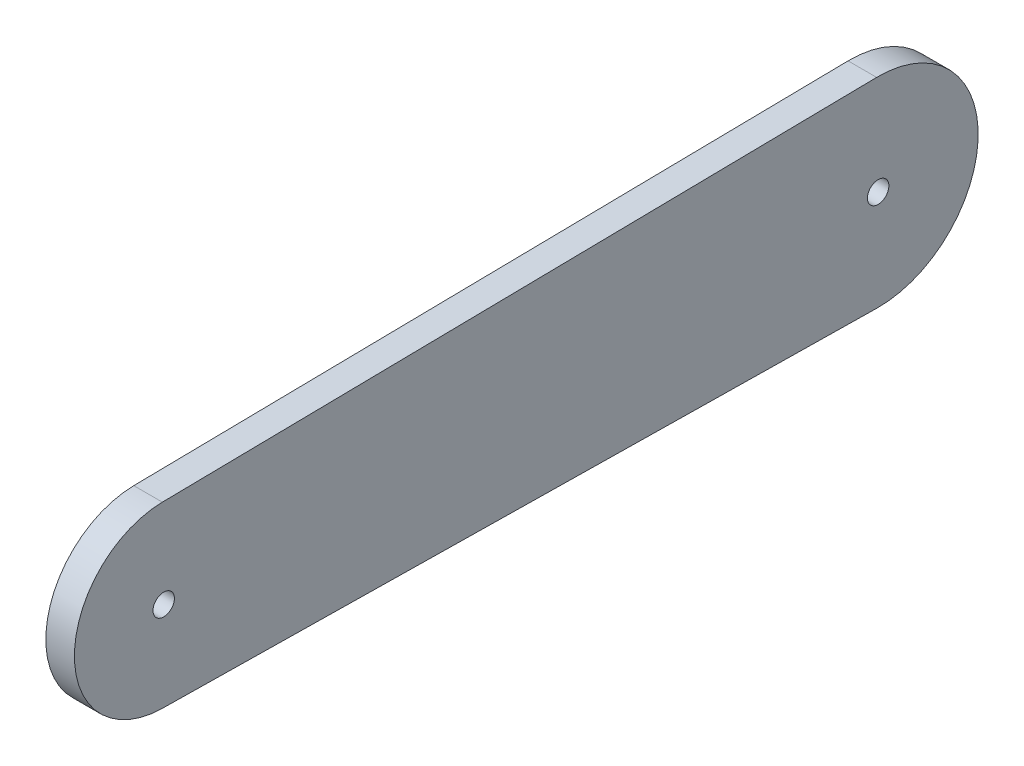
SolidWorks part; units mm, degrees
ref_plane "Alzado" through (0, 0, 0) normal (0, 0, 1) x (1, 0, 0)
ref_plane "Planta" through (0, 0, 0) normal (0, 1, 0) x (1, 0, 0)
ref_plane "Vista lateral" through (0, 0, 0) normal (1, 0, 0) x (0, 0, -1)
sketch "Croquis1" plane through (0, 0, 0) normal (1, 0, 0) x (0, 0, -1)
  line L0 (0, 0) -> (-98.2419, 0) construction
  line L1 (-100.1875, 12.4986) -> (-0.21, 13.9984)
  line L2 (-100.1875, -12.4986) -> (-0.21, -13.9984)
  circle A0 centre (0, 0) radius 1.5
  arc A1 (-0.21, -13.9984) -> (-0.21, 13.9984) centre (0, 0) ccw
  circle A2 centre (-100, 0) radius 1.5
  arc A3 (-100.1875, 12.4986) -> (-100.1875, -12.4986) centre (-100, 0) ccw
  dimension "D1" = 3
  dimension "D2" = 28
  dimension "D3" = 25
  dimension "D4" = 100
  dimension "D5" = 3
extrude "Saliente-Extruir1" add sketch "Croquis1" along normal blind 4
